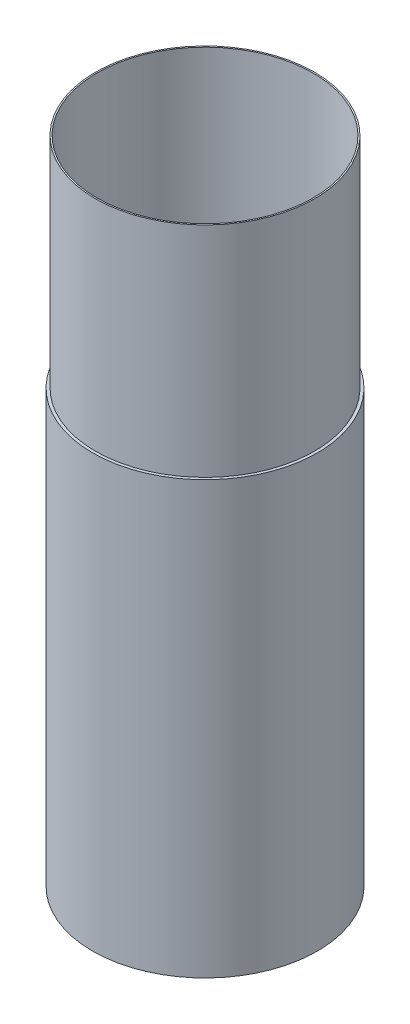
SolidWorks part; units mm, degrees
material "A-Glass Fiber"
ref_plane "Front Plane" through (0, 0, 0) normal (0, 0, 1) x (1, 0, 0)
ref_plane "Top Plane" through (0, 0, 0) normal (0, 1, 0) x (1, 0, 0)
ref_plane "Right Plane" through (0, 0, 0) normal (1, 0, 0) x (0, 0, -1)
sketch "Sketch1" plane through (0, 0, 0) normal (0, 0, 1) x (1, 0, 0)
  line L0 (78.16, 0) -> (78.16, 300)
  line L1 (76.2, 0) -> (76.2, 300)
  line L2 (78.16, 300) -> (76.2, 300)
  line L3 (76.2, 0) -> (78.16, 0)
  line L4 (0, 204.6154) -> (0, 85.8935) construction
  dimension "D1" = 76.2
  dimension "D2" = 300
  dimension "D3" = 1.96
revolve "Revolve1" add sketch "Sketch1" angle 360 about L4
sketch "Sketch3" plane through (0, 300, 0) normal (0, 1, 0) x (1, 0, 0)
  circle A2 centre (0, 0) radius 76.2 construction
  circle A3 centre (0, 0) radius 76.2
  circle A4 centre (0, 0) radius 75.2
  dimension "D1" = 1
extrude "Boss-Extrude1" add sketch "Sketch3" along normal blind 152 and the other way blind 152
